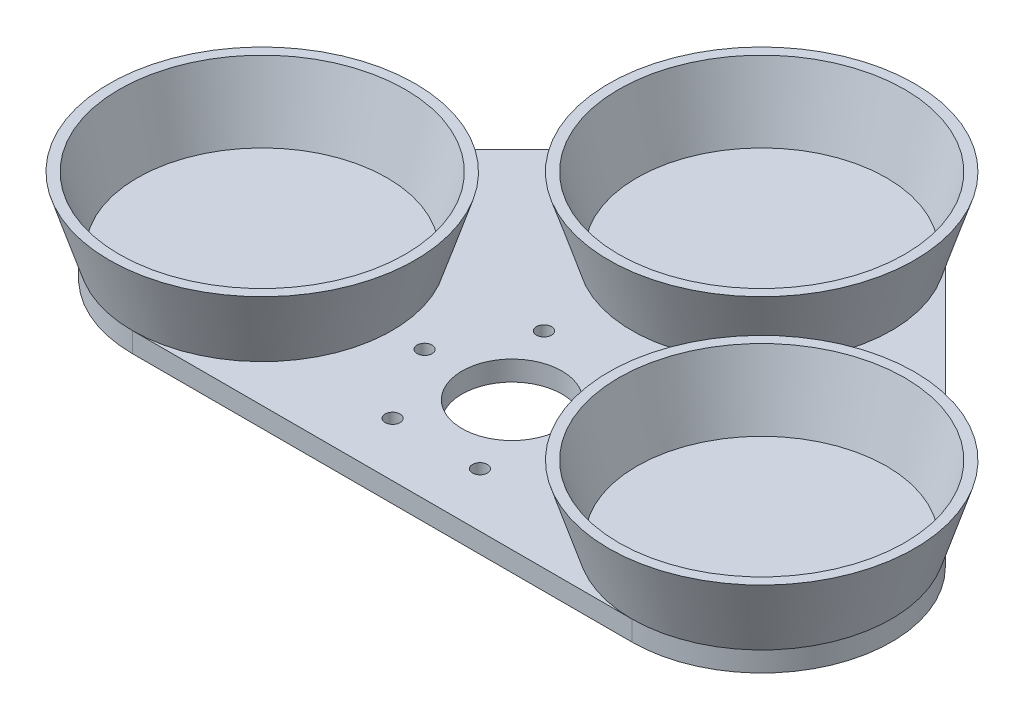
SolidWorks part; units mm, degrees
material "聚脂树脂"
ref_plane "前视基准面" through (0, 0, 0) normal (0, 0, 1) x (1, 0, 0)
ref_plane "上视基准面" through (0, 0, 0) normal (0, 1, 0) x (1, 0, 0)
ref_plane "右视基准面" through (0, 0, 0) normal (1, 0, 0) x (0, 0, -1)
other "Configuration Table"
sketch "草图1" plane through (0, 0, 0) normal (0, 1, 0) x (1, 0, 0)
  line L0 (0, 0) -> (0, 49.6717) construction
  line L1 (0, 0) -> (71.6532, 0) construction
  line L2 (0, 0) -> (-79.8556, 0) construction
  circle A0 centre (0, 50) radius 26
  circle A1 centre (50, 0) radius 26
  circle A2 centre (-50, 0) radius 26
  dimension "D1" = 52
  dimension "D2" = 52
  dimension "D3" = 52
  dimension "D4" = 50
  dimension "D5" = 50
  dimension "D6" = 50
extrude "凸台-拉伸1" add sketch "草图1" along normal blind 1
sketch "草图2" plane through (0, 0, 0) normal (0, -1, 0) x (1, 0, 0)
  line L0 (-50, 26) -> (50, 26)
  line L1 (0, 0) -> (0, 33.5546) construction
  line L2 (-73.6118, 0) -> (73.6118, 0) construction
  line L3 (-68.3848, -18.3848) -> (-18.3848, -68.3848)
  line L4 (-50, 0) -> (0, -50) construction
  line L5 (0, -50) -> (-23.3411, -73.3411) construction
  line L6 (-23.3411, -73.3411) -> (-73.3411, -23.3411) construction
  line L7 (-73.3411, -23.3411) -> (-50, 0) construction
  line L8 (68.3848, -18.3848) -> (18.3848, -68.3848)
  line L9 (-50, 0) -> (-50, 39.8506) construction
  line L10 (50, 0) -> (50, 45.3726) construction
  circle A0 centre (-50, 0) radius 26 construction
  circle A1 centre (50, 0) radius 26 construction
  circle A2 centre (0, -50) radius 26 construction
  arc A3 (-68.3848, -18.3848) -> (-50, 26) centre (-50, 0) cw
  arc A4 (50, 26) -> (68.3848, -18.3848) centre (50, 0) cw
  arc A5 (18.3848, -68.3848) -> (-18.3848, -68.3848) centre (0, -50) cw
  circle A6 centre (0, 0) radius 10
  circle M5 centre (50, 0) radius 26
  dimension "D1" = 20
extrude "凸台-拉伸2" add sketch "草图2" along normal blind 4 contours A5 L8 L0 A3 L3 M5 | M5
sketch "草图3" plane through (0, 0, 0) normal (0, 1, 0) x (1, 0, 0)
  line L0 (0, 0) -> (23.7238, 41.0908) construction
  line L1 (0, 0) -> (0, 31.7505) construction
  line L2 (0, 0) -> (31.2503, 0) construction
  circle A1 centre (8.75, 15.1554) radius 1.5
  circle A2 centre (17.5, 0) radius 1.5
  circle A3 centre (-17.5, 0) radius 1.5
  circle A4 centre (-8.75, 15.1554) radius 1.5
  circle A5 centre (-8.75, -15.1554) radius 1.5
  circle A6 centre (8.75, -15.1554) radius 1.5
  dimension "D3" = 3
  dimension "D4" = 3
  dimension "D6" = 17.5
  dimension "D2" = 60
  dimension "D5" = 17.5
extrude "切除-拉伸1" cut sketch "草图3" against normal blind 4
sketch "草图4" plane through (0, 0, 0) normal (1, 0, 0) x (0, 0, -1)
  line L0 (0, 0) -> (0, 27.6583) construction
  line L1 (0, 0) -> (83.286, 0) construction
  line L3 (76, 1) -> (24, 1) construction
  line L5 (80.6235, 14.523) -> (78.6235, 14.523)
  line L6 (78.6235, 14.523) -> (75, 1)
  line L7 (75, 1) -> (50, 1) construction
  line L8 (75, 1) -> (75, 24.8848) construction
  line L9 (50, 1) -> (50, 31.3753) construction
  line L10 (75, 1) -> (76, 1)
  line L11 (76, 1) -> (76, 0)
  line L12 (76, -4) -> (76, 1) construction
  line L13 (76, 0) -> (80.6235, 14.523)
  dimension "D1" = 14
  dimension "D2" = 25
  dimension "D3" = 15
  dimension "D4" = 2
  dimension "D5" = 1
revolve "旋转1" add sketch "草图4" angle 360 about L9
sketch "草图6" plane through (0, 0, 0) normal (0, 0, 1) x (1, 0, 0)
  line L0 (-50, 1) -> (-50, 34.4224) construction
  line L1 (-24, 1) -> (-76, 1) construction
  line L2 (50, 1) -> (50, 41.1421) construction
  line L3 (76, 1) -> (24, 1) construction
  line L4 (-75, 1) -> (-78.6235, 14.523)
  line L5 (-78.6235, 14.523) -> (-80.6235, 14.523)
  line L8 (-76, 1) -> (-75, 1)
  line L9 (-75, 1) -> (-75, 30.7819) construction
  line L10 (-76, 1) -> (-76, 0)
  line L11 (-76, 1) -> (-76, -4) construction
  line L12 (-76, 0) -> (-80.6235, 14.523)
  dimension "D1" = 1
  dimension "D2" = 2
  dimension "D3" = 15
  dimension "D4" = 14
  dimension "D5" = 1
revolve "旋转2" add sketch "草图6" angle 360 about L0
sketch "草图7" plane through (0, 0, 0) normal (0, 0, 1) x (1, 0, 0)
  line L0 (50, 1) -> (50, 30.1394) construction
  line L2 (76, 1) -> (24, 1) construction
  line L3 (75, 1) -> (76, 1)
  line L4 (76, 1) -> (76, 0)
  line L5 (76, 0) -> (80.6235, 14.523)
  line L6 (80.6235, 14.523) -> (78.6235, 14.523)
  line L7 (78.6235, 14.523) -> (75, 1)
  line L8 (75, 1) -> (75, 24.7143) construction
  dimension "D1" = 2
  dimension "D2" = 1
  dimension "D3" = 1
  dimension "D4" = 14
  dimension "D5" = 15
revolve "旋转3" add sketch "草图7" angle 360 about L0
